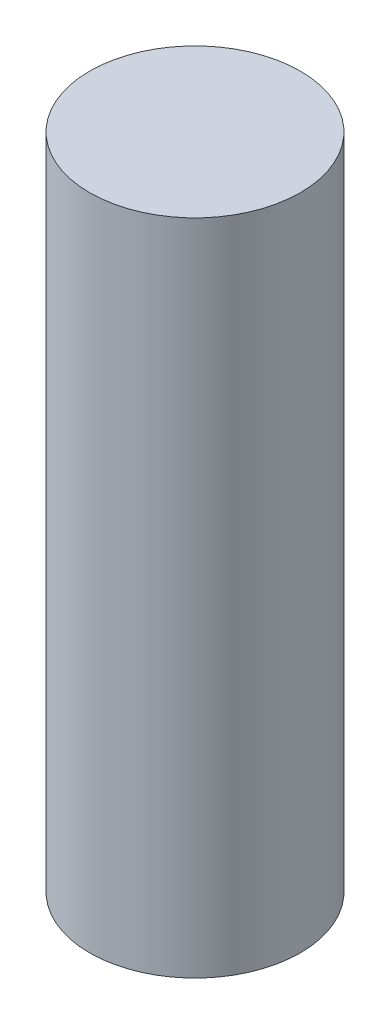
SolidWorks part; units mm, degrees
material "6061 Alloy"
ref_plane "Front Plane" through (0, 0, 0) normal (0, 0, 1) x (1, 0, 0)
ref_plane "Top Plane" through (0, 0, 0) normal (0, 1, 0) x (1, 0, 0)
ref_plane "Right Plane" through (0, 0, 0) normal (1, 0, 0) x (0, 0, -1)
sketch "Sketch1" plane through (0, 0, 0) normal (0, 1, 0) x (1, 0, 0)
  circle A0 centre (0, 0) radius 4
  dimension "D1" = 8
extrude "Boss-Extrude1" add sketch "Sketch1" along normal blind 25
equation "\"____ GENERATED PART EXPORTS ____\" = 0"
equation "\"SYS_VersionTag\" = 2"
equation "\"EXT_Dia\" = 8mm"
equation "\"EXT_RodCutLength\" = 25mm"
equation "\"D1@Sketch1\"=\"EXT_Dia\""
equation "\"D1@Boss-Extrude1\"=\"EXT_RodCutLength\""
